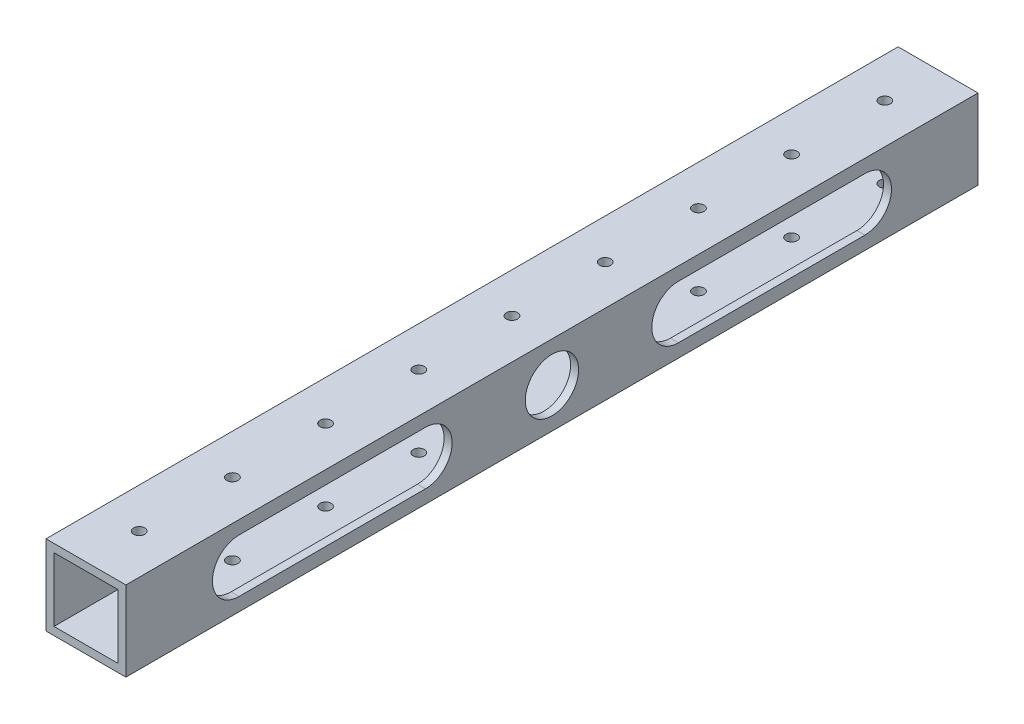
SolidWorks part; units mm, degrees
material "6061 合金"
ref_plane "前视基准面" through (0, 0, 0) normal (0, 0, 1) x (1, 0, 0)
ref_plane "上视基准面" through (0, 0, 0) normal (0, 1, 0) x (1, 0, 0)
ref_plane "右视基准面" through (0, 0, 0) normal (1, 0, 0) x (0, 0, -1)
sketch "草图1" plane through (0, 0, 0) normal (0, 0, 1) x (1, 0, 0)
  line L1 (0, 0) -> (30, 0)
  line L2 (0, 0) -> (0, 30)
  line L3 (0, 30) -> (30, 30)
  line L4 (30, 0) -> (30, 30)
  dimension "D1" = 30
  dimension "D2" = 30
extrude "拉伸-薄壁1" add sketch "草图1" along normal blind 320 thin thin type one direction reverse wall 3
sketch "草图2" plane through (30, 0, 0) normal (1, 0, 0) x (0, 0, -1)
  line L0 (-160, 30) -> (-160, 0) construction
  line L1 (-320, 30) -> (0, 30) construction
  line L2 (-320, 0) -> (0, 0) construction
  line L3 (-320, 15) -> (0, 15) construction
  line L4 (-320, 0) -> (-320, 30) construction
  line L5 (0, 0) -> (0, 30) construction
  line L6 (-242.5, 0) -> (-242.5, 30) construction
  line L7 (-277.5, 15) -> (-207.5, 15) construction
  line L8 (-277.5, 25) -> (-207.5, 25)
  line L9 (-277.5, 5) -> (-207.5, 5)
  line L10 (-42.5, 15) -> (-112.5, 15) construction
  line L11 (-42.5, 25) -> (-112.5, 25)
  line L12 (-42.5, 5) -> (-112.5, 5)
  circle A0 centre (-160, 15) radius 10
  arc A1 (-277.5, 25) -> (-277.5, 5) centre (-277.5, 15) ccw
  arc A2 (-207.5, 5) -> (-207.5, 25) centre (-207.5, 15) ccw
  arc A3 (-42.5, 25) -> (-42.5, 5) centre (-42.5, 15) cw
  arc A4 (-112.5, 5) -> (-112.5, 25) centre (-112.5, 15) cw
  point P14 (-242.5, 15)
  point P17 (-242.5, 15)
  point P20 (-242.5, 15)
  point P27 (-77.5, 15)
  dimension "D1" = 82.5
  dimension "D2" = 30
  dimension "D3" = 20
  dimension "D4" = 70
extrude "切除-拉伸1" cut sketch "草图2" against normal through all
sketch "草图3" plane through (0, 30, 0) normal (0, 1, 0) x (1, 0, 0)
  line L0 (0, -160) -> (30, -160) construction
  line L1 (0, -320) -> (0, 0) construction
  line L2 (30, -320) -> (30, 0) construction
  line L3 (15, 0) -> (15, -320) construction
  line L4 (30, 0) -> (0, 0) construction
  line L5 (30, -320) -> (0, -320) construction
  circle A0 centre (15, -20) radius 2.1
  circle A1 centre (15, -55) radius 2.1
  circle A2 centre (15, -90) radius 2.1
  circle A3 centre (15, -125) radius 2.1
  circle A4 centre (15, -300) radius 2.1
  circle A5 centre (15, -265) radius 2.1
  circle A6 centre (15, -230) radius 2.1
  circle A7 centre (15, -195) radius 2.1
  circle A8 centre (15, -160) radius 2.1
  dimension "D1" = 20
  dimension "D2" = 35
  dimension "D3" = 35
  dimension "D4" = 35
  dimension "D5" = 35
  dimension "D6" = 160
extrude "切除-拉伸2" cut sketch "草图3" against normal through all
